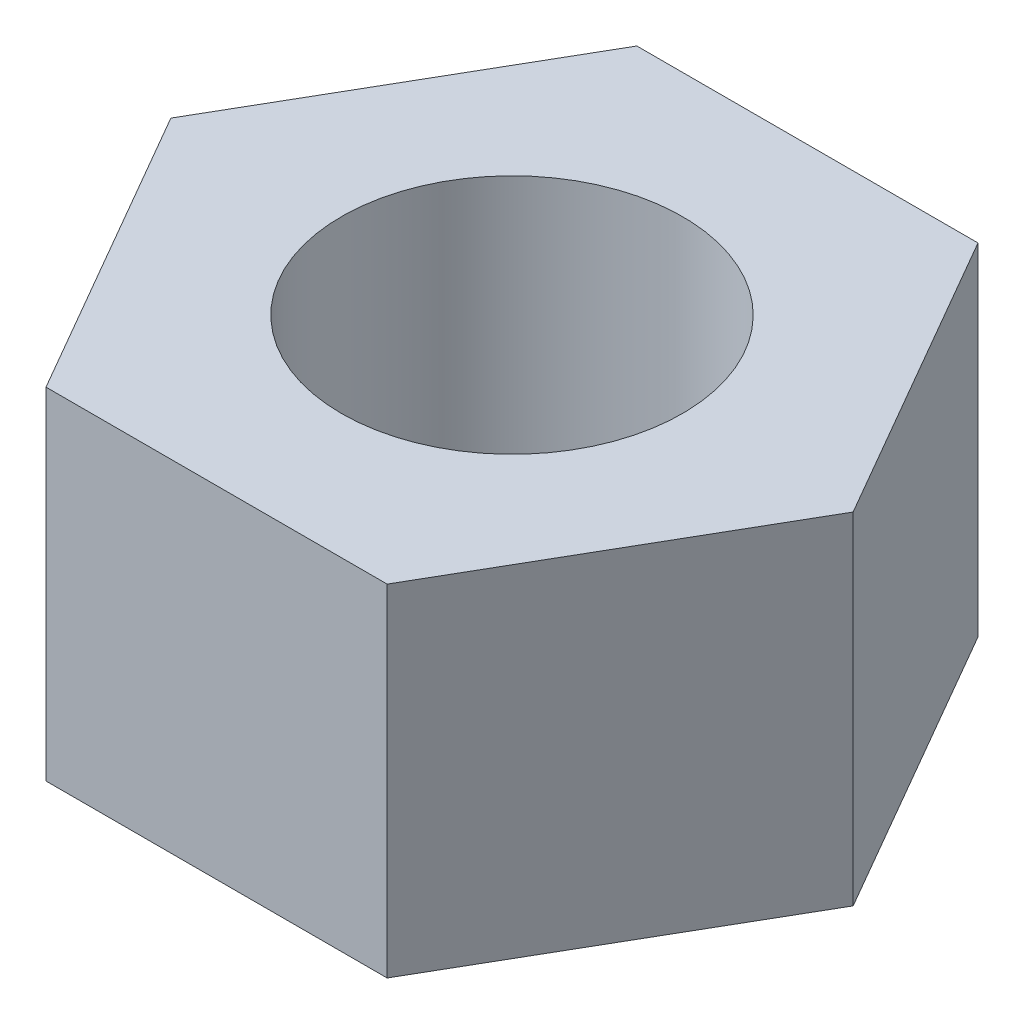
SolidWorks part; units mm, degrees
ref_plane "Plan de face" through (0, 0, 0) normal (0, 0, 1) x (1, 0, 0)
ref_plane "Plan de dessus" through (0, 0, 0) normal (0, 1, 0) x (1, 0, 0)
ref_plane "Plan de droite" through (0, 0, 0) normal (1, 0, 0) x (0, 0, -1)
sketch "Esquisse1" plane through (0, 0, 0) normal (0, 1, 0) x (1, 0, 0)
  line L0 (-10, 17.3205) -> (10, 17.3205)
  line L1 (10, 17.3205) -> (20, 0)
  line L2 (20, 0) -> (10, -17.3205)
  line L3 (10, -17.3205) -> (-10, -17.3205)
  line L4 (-10, -17.3205) -> (-20, 0)
  line L5 (-10, 17.3205) -> (-20, 0)
  line L6 (-20, 0) -> (20, 0) construction
  line L7 (-10, -17.3205) -> (10, 17.3205) construction
  line L8 (10, -17.3205) -> (-10, 17.3205) construction
  circle A0 centre (0, 0) radius 10
  point P2 (0, 0)
  dimension "D1" = 20
extrude "Boss.-Extru.1" add sketch "Esquisse1" along normal blind 20
